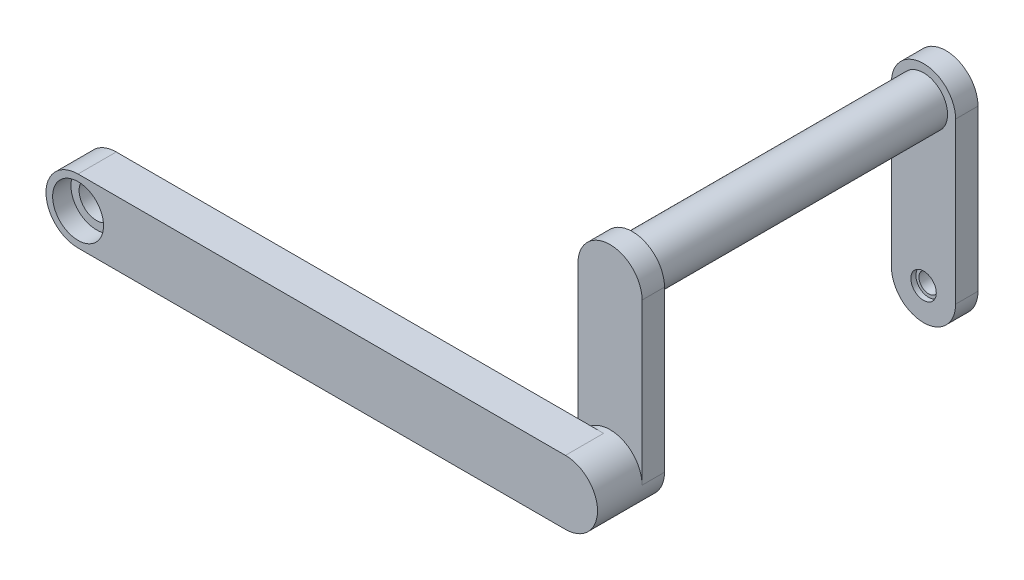
SolidWorks part; units mm, degrees
ref_plane "Alzado" through (0, 0, 0) normal (0, 0, 1) x (1, 0, 0)
ref_plane "Planta" through (0, 0, 0) normal (0, 1, 0) x (1, 0, 0)
ref_plane "Vista lateral" through (0, 0, 0) normal (1, 0, 0) x (0, 0, -1)
sketch "Croquis1" plane through (0, 0, 0) normal (0, 0, 1) x (1, 0, 0)
  line L0 (0, 0) -> (47.88, 0) construction
  line L1 (0, 3.15) -> (47.88, 3.15)
  line L2 (0, -3.15) -> (47.88, -3.15)
  circle A0 centre (0, 0) radius 1.7
  arc A1 (0, 3.15) -> (0, -3.15) centre (0, 0) ccw
  arc A2 (47.88, -3.15) -> (47.88, 3.15) centre (47.88, 0) ccw
  dimension "D2" = 3.4
  dimension "D3" = 6.3
  dimension "D4" = 6.3
  dimension "D1" = 47.88
extrude "Saliente-Extruir1" add sketch "Croquis1" along normal blind 3.75
sketch "Croquis2" plane through (0, 0, 0) normal (0, 0, -1) x (-1, 0, 0)
  circle A0 centre (-47.88, 0) radius 3.15
  arc A1 (-47.88, 3.15) -> (-47.88, -3.15) centre (-47.88, 0) ccw construction
extrude "Saliente-Extruir2" add sketch "Croquis2" along normal blind 0.63
sketch "Croquis4" plane through (0, 0, 3.75) normal (0, 0, 1) x (1, 0, 0)
  circle A0 centre (0, 0) radius 2.5
  dimension "D1" = 5
extrude "Cortar-Extruir1" cut sketch "Croquis4" against normal blind 1.8
sketch "Croquis5" plane through (0, 0, -0.63) normal (0, 0, -1) x (-1, 0, 0)
  line L0 (-47.88, 0) -> (-47.88, 15.75) construction
  line L1 (-51.03, 15.75) -> (-51.03, 0)
  line L2 (-44.73, 15.75) -> (-44.73, 0)
  arc A0 (-51.03, 0) -> (-44.73, 0) centre (-47.88, 0) ccw
  arc A1 (-44.73, 15.75) -> (-51.03, 15.75) centre (-47.88, 15.75) ccw
  dimension "D2" = 6.3
  dimension "D1" = 15.75
extrude "Saliente-Extruir3" add sketch "Croquis5" along normal blind 2.2
sketch "Croquis6" plane through (0, 0, -2.83) normal (0, 0, -1) x (-1, 0, 0)
  circle A0 centre (-47.88, 15.75) radius 2.3625
  dimension "D1" = 4.725
extrude "Saliente-Extruir4" add sketch "Croquis6" along normal blind 28.6
sketch "Croquis7" plane through (0, 0, -31.43) normal (0, 0, -1) x (-1, 0, 0)
  line L0 (-51.03, 15.75) -> (-51.03, 0)
  line L1 (-44.73, 15.75) -> (-44.73, 0)
  arc A0 (-44.73, 15.75) -> (-51.03, 15.75) centre (-47.88, 15.75) ccw
  arc A1 (-51.03, 0) -> (-44.73, 0) centre (-47.88, 0) ccw
  circle A2 centre (-47.88, 0) radius 0.95
  dimension "D1" = 1.9
extrude "Saliente-Extruir5" add sketch "Croquis7" along normal blind 2.2
sketch "Croquis8" plane through (0, 0, -31.43) normal (0, 0, 1) x (1, 0, 0)
  circle A0 centre (47.88, 0) radius 1.25
  dimension "D1" = 2.5
extrude "Cortar-Extruir2" cut sketch "Croquis8" against normal blind 0.5
